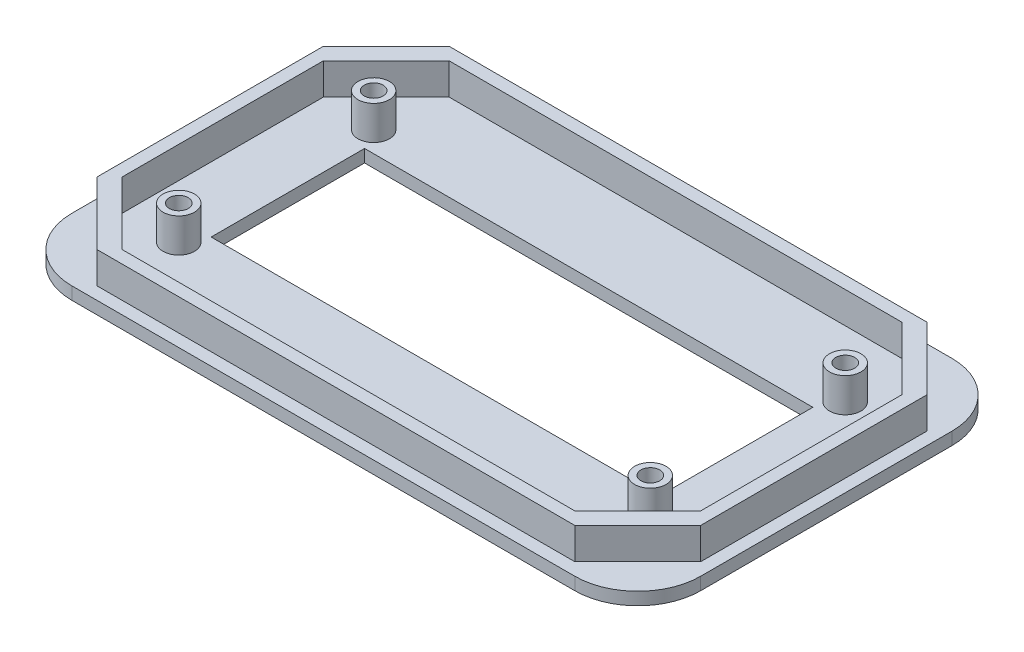
SolidWorks part; units mm, degrees
ref_plane "Ön Düzlem" through (0, 0, 0) normal (0, 0, 1) x (1, 0, 0)
ref_plane "Üst Düzlem" through (0, 0, 0) normal (0, 1, 0) x (1, 0, 0)
ref_plane "Sağ Düzlem" through (0, 0, 0) normal (1, 0, 0) x (0, 0, -1)
sketch "Çizim1" plane through (0, 0, 0) normal (0, 1, 0) x (1, 0, 0)
  line L1 (10, 0) -> (90, 0)
  line L2 (0, 10) -> (0, 50)
  line L3 (10, 60) -> (90, 60)
  line L4 (100, 10) -> (100, 50)
  arc A0 (90, 60) -> (100, 50) centre (90, 50) cw
  arc A1 (90, 0) -> (100, 10) centre (90, 10) ccw
  arc A2 (10, 0) -> (0, 10) centre (10, 10) cw
  arc A3 (0, 50) -> (10, 60) centre (10, 50) cw
  point P7 (100, 60)
  point P12 (0, 0)
  point P15 (0, 60)
  dimension "D3" = 10
  dimension "D1" = 60
  dimension "D2" = 100
extrude "Yükseklik-Ekstrüzyon1" add sketch "Çizim1" along normal blind 2
sketch "Çizim2" plane through (0, 2, 0) normal (0, 1, 0) x (1, 0, 0)
  line L0 (12, 58) -> (12, 2) construction
  line L1 (0, 0) -> (100, 0) construction
  line L2 (0, 0) -> (0, 60) construction
  line L3 (0, 60) -> (100, 60) construction
  line L4 (100, 0) -> (100, 60) construction
  line L5 (12, 2) -> (88, 2)
  line L6 (2, 12) -> (2, 48)
  line L7 (12, 58) -> (88, 58)
  line L8 (98, 12) -> (98, 48)
  line L9 (2, 48) -> (98, 48) construction
  line L10 (12, 58) -> (2, 48)
  line L11 (50, 58) -> (50, 2) construction
  line L12 (2, 30) -> (98, 30) construction
  line L13 (88, 58) -> (98, 48)
  line L14 (88, 2) -> (98, 12)
  line L15 (12, 2) -> (2, 12)
  line L16 (86, 56) -> (86, 4) construction
  line L18 (4, 46) -> (4, 14)
  line L19 (14, 4) -> (86, 4)
  line L21 (96, 14) -> (61.1736, 14) construction
  line L22 (96, 14) -> (86, 4)
  line L23 (96, 46) -> (86, 56)
  line L24 (4, 14) -> (14, 4)
  line L25 (4, 46) -> (14, 56)
  line L26 (96, 46) -> (96, 14)
  line L27 (14, 56) -> (86, 56)
  dimension "D1" = 60
  dimension "D2" = 100
  dimension "D5" = 2
  dimension "D6" = 2
  dimension "D7" = 10
  dimension "D8" = 10
  dimension "D9" = 2
  dimension "D10" = 2
  dimension "D12" = 10
extrude "Yükseklik-Ekstrüzyon2" add sketch "Çizim2" along normal blind 5
sketch "Çizim3" plane through (0, 2, 0) normal (0, 1, 0) x (1, 0, 0)
  line L0 (50, 48) -> (50, 12) construction
  line L3 (14.35, 42.2) -> (85.65, 42.2)
  line L6 (4, 46) -> (4, 14) construction
  line L7 (10, 48) -> (90, 48) construction
  line L8 (10, 48) -> (10, 12) construction
  line L9 (10, 12) -> (90, 12) construction
  line L10 (90, 48) -> (90, 12) construction
  line L11 (86, 56) -> (14, 56) construction
  line L12 (14.35, 42.2) -> (14.35, 17.8)
  line L13 (14.35, 17.8) -> (85.65, 17.8)
  line L14 (85.65, 42.2) -> (85.65, 17.8)
  line L15 (10, 30) -> (90, 30) construction
  line L16 (50, 42.2) -> (50, 17.8) construction
  line L17 (14.35, 30) -> (85.65, 30) construction
  point P12 (50, 30)
  dimension "D1" = 80
  dimension "D2" = 36
  dimension "D3" = 6
  dimension "D4" = 8
  dimension "D5" = 71.3
  dimension "D6" = 24.4
  dimension "D7" = 0
  dimension "D8" = 0
extrude "Kes-Ekstrüzyon1" cut sketch "Çizim3" against normal blind 5
sketch "Çizim4" plane through (0, 2, 0) normal (0, 1, 0) x (1, 0, 0)
  line L0 (4, 46) -> (4, 14) construction
  line L1 (10, 48) -> (90, 48) construction
  line L2 (10, 48) -> (10, 12) construction
  line L3 (10, 12) -> (90, 12) construction
  line L4 (90, 48) -> (90, 12) construction
  line L5 (86, 56) -> (14, 56) construction
  line L6 (50, 48) -> (50, 12) construction
  line L7 (10, 30) -> (90, 30) construction
  circle A0 centre (12.5, 45.5) radius 1.5
  circle A1 centre (87.5, 45.5) radius 1.5
  circle A2 centre (87.5, 14.5) radius 1.5
  circle A3 centre (12.5, 14.5) radius 1.5
  circle A4 centre (12.5, 45.5) radius 2.5
  circle A5 centre (87.5, 45.5) radius 2.5
  circle A6 centre (87.5, 14.5) radius 2.5
  circle A7 centre (12.5, 14.5) radius 2.5
  dimension "D5" = 3
  dimension "D1" = 80
  dimension "D2" = 36
  dimension "D3" = 6
  dimension "D4" = 8
  dimension "D6" = 2.5
  dimension "D7" = 2.5
extrude "Yükseklik-Ekstrüzyon3" add sketch "Çizim4" along normal blind 5.4
